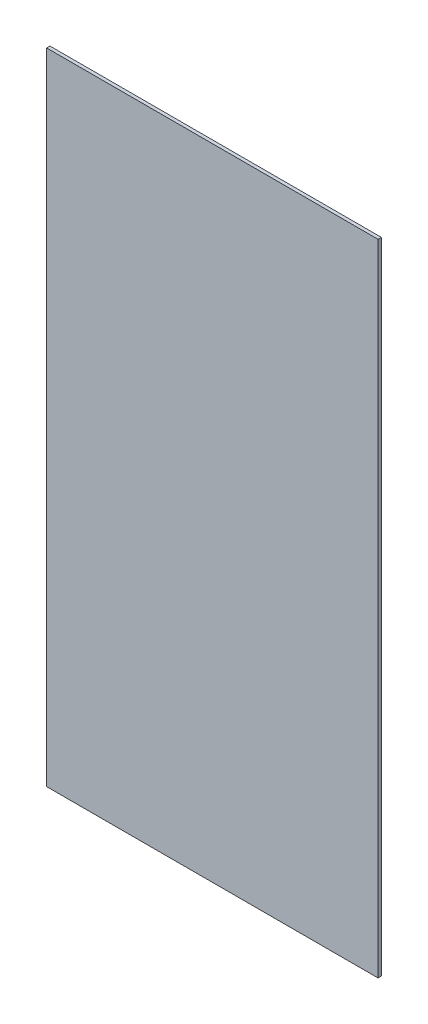
SolidWorks part; units mm, degrees
ref_plane "Front Plane" through (0, 0, 0) normal (0, 0, 1) x (1, 0, 0)
ref_plane "Top Plane" through (0, 0, 0) normal (0, 1, 0) x (1, 0, 0)
ref_plane "Right Plane" through (0, 0, 0) normal (1, 0, 0) x (0, 0, -1)
sketch "Sketch1" plane through (0, 0, 0) normal (0, 0, 1) x (1, 0, 0)
  line L1 (150, -289.5) -> (-150, -289.5)
  line L2 (150, -289.5) -> (150, 289.5)
  line L3 (150, 289.5) -> (-150, 289.5)
  line L4 (-150, -289.5) -> (-150, 289.5)
  line L5 (150, -289.5) -> (-150, 289.5) construction
  line L6 (150, 289.5) -> (-150, -289.5) construction
  point P0 (0, 0)
  dimension "D1" = 300
  dimension "D2" = 579
extrude "Boss-Extrude1" add sketch "Sketch1" along normal mid plane 3
